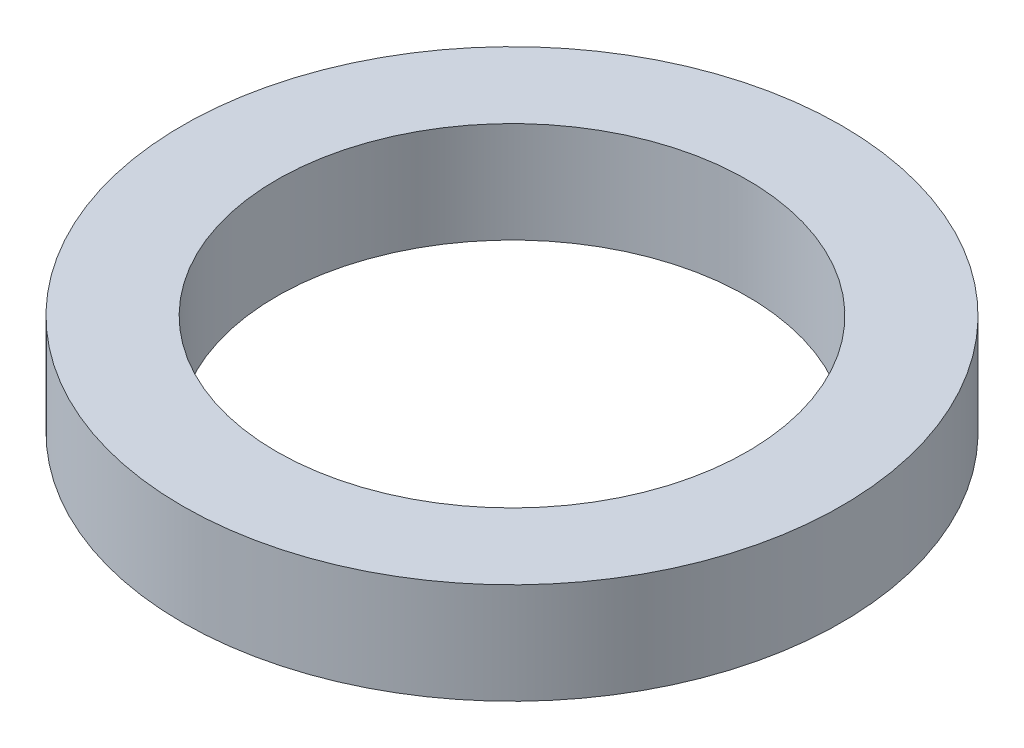
SolidWorks part; units mm, degrees
ref_plane "Front Plane" through (0, 0, 0) normal (0, 0, 1) x (1, 0, 0)
ref_plane "Top Plane" through (0, 0, 0) normal (0, 1, 0) x (1, 0, 0)
ref_plane "Right Plane" through (0, 0, 0) normal (1, 0, 0) x (0, 0, -1)
sketch "Sketch1" plane through (0, 0, 0) normal (0, 1, 0) x (1, 0, 0)
  circle A0 centre (0, 0) radius 3.5
  circle A1 centre (0, 0) radius 4.9
  dimension "D1" = 7
  dimension "D2" = 9.8
extrude "Boss-Extrude1" add sketch "Sketch1" along normal blind 1.5
